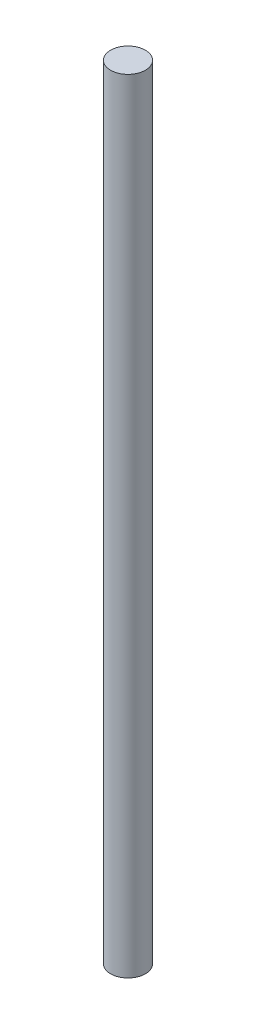
SolidWorks part; units mm, degrees
material "Balsa"
ref_plane "Front Plane" through (0, 0, 0) normal (0, 0, 1) x (1, 0, 0)
ref_plane "Top Plane" through (0, 0, 0) normal (0, 1, 0) x (1, 0, 0)
ref_plane "Right Plane" through (0, 0, 0) normal (1, 0, 0) x (0, 0, -1)
sketch "Sketch1" plane through (0, 0, 0) normal (0, 1, 0) x (1, 0, 0)
  circle A0 centre (0, 0) radius 3
extrude "Boss-Extrude1" add sketch "Sketch1" along normal mid plane 135
